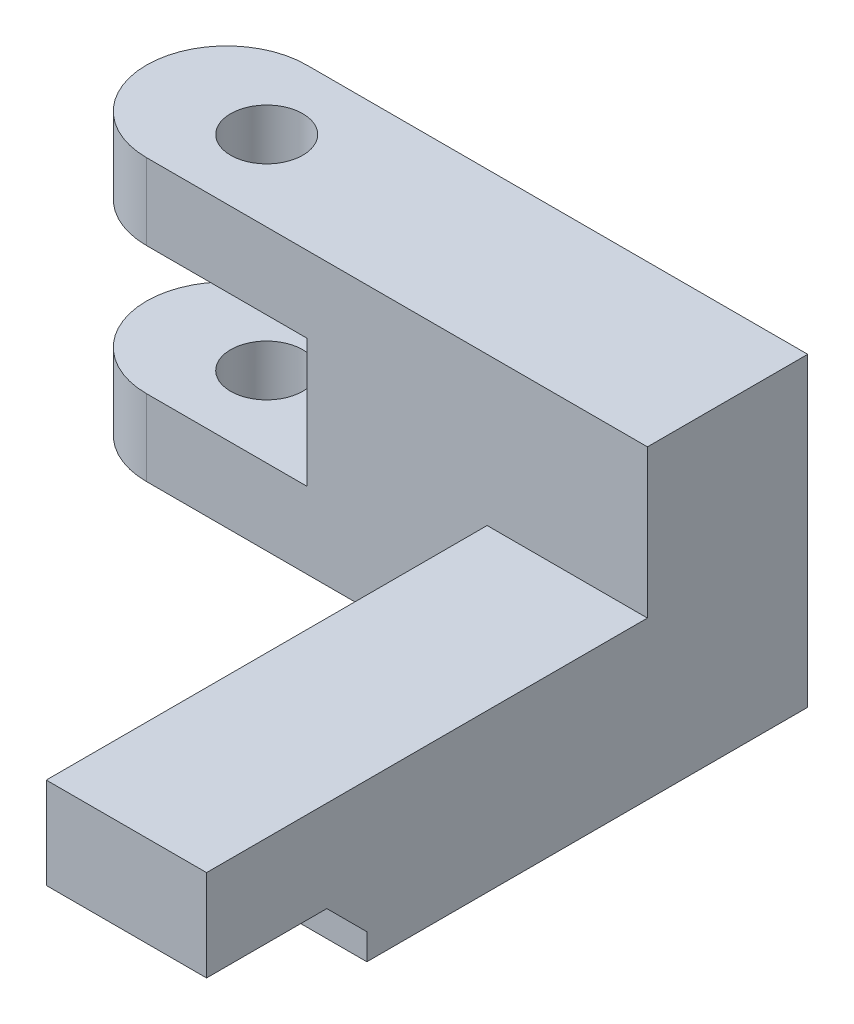
SolidWorks part; units mm, degrees
ref_plane "Front Plane" through (0, 0, 0) normal (0, 0, 1) x (1, 0, 0)
ref_plane "Top Plane" through (0, 0, 0) normal (0, 1, 0) x (1, 0, 0)
ref_plane "Right Plane" through (0, 0, 0) normal (1, 0, 0) x (0, 0, -1)
sketch "Sketch1" plane through (0, 0, 0) normal (0, 1, 0) x (1, 0, 0)
  line L1 (1.4969, 0) -> (13.9969, 0)
  line L3 (1.4969, -4) -> (9.9969, -4)
  line L5 (13.9969, 0) -> (13.9969, -15)
  line L10 (2.4969, -2) -> (13.9969, -2) construction
  line L11 (9.9969, -15) -> (13.9969, -15)
  line L16 (9.9969, -4) -> (9.9969, -15)
  circle A0 centre (2.4969, -2) radius 0.9
  arc A2 (1.4969, -4) -> (1.4969, 0) centre (1.4969, -2) cw
  dimension "D3" = 1.8
  dimension "D2" = 2
  dimension "D1" = 8.5
  dimension "D4" = 4
  dimension "D5" = 4
  dimension "D6" = 15
  dimension "D7" = 1
extrude "Boss-Extrude1" add sketch "Sketch1" along normal blind 7
sketch "Sketch2" plane through (0, 0, 4) normal (0, 0, 1) x (1, 0, 0)
  line L0 (1.4969, 7) -> (-0.5031, 7) construction
  line L1 (-0.5031, 1.9) -> (5.4969, 1.9)
  line L2 (-0.5031, 1.9) -> (-0.5031, 5.1)
  line L3 (-0.5031, 5.1) -> (5.4969, 5.1)
  line L4 (5.4969, 1.9) -> (5.4969, 5.1)
  line L5 (2.4969, 5.1) -> (2.4969, 1.9) construction
  line L6 (-0.5031, 3.5) -> (5.4969, 3.5) construction
  line L7 (-0.5031, 7) -> (-0.5031, 0) construction
  line L8 (-0.5031, 7) -> (-0.5031, 0) construction
  line L9 (-0.5031, 0) -> (1.4969, 0) construction
  point P6 (-0.5031, 3.5)
  point P228 (2.4969, 3.5)
  dimension "D1" = 3.2
  dimension "D2" = 6
extrude "Cut-Extrude1" cut sketch "Sketch2" against normal up to next
sketch "Sketch3" plane through (13.9969, 0, 0) normal (1, 0, 0) x (0, 0, -1)
  line L8 (-15, 3.5) -> (0, 3.5) construction
  line L9 (0, 7) -> (0, 0) construction
  line L14 (-15, 7) -> (-15, 0) construction
  line L16 (-15, 7) -> (-4, 7)
  line L17 (-15, 7) -> (-15, 3.3)
  line L18 (-15, 3.3) -> (-4, 3.3)
  line L19 (-4, 7) -> (-4, 3.3)
  line L20 (-9.5, 3.3) -> (-9.5, 7) construction
  line L21 (-15, 5.15) -> (-4, 5.15) construction
  point P230 (-9.5, 5.15)
  dimension "D1" = 4
  dimension "D2" = 0.2
extrude "Cut-Extrude2" cut sketch "Sketch3" against normal blind 4
sketch "Sketch6" plane through (0, 0, 0) normal (0, -1, 0) x (1, 0, 0)
  line L0 (9.9969, 4) -> (9.9969, 15) construction
  line L1 (13.9969, 0) -> (9.9969, 0)
  line L2 (13.9969, 0) -> (13.9969, 15)
  line L3 (13.9969, 15) -> (9.9969, 15)
  line L4 (9.9969, 0) -> (9.9969, 15)
  line L5 (11.9969, 15) -> (11.9969, 0) construction
  line L6 (13.9969, 7.5) -> (9.9969, 7.5) construction
  line L7 (9.9969, 15) -> (13.9969, 15) construction
  point P108 (11.9969, 7.5)
extrude "Boss-Extrude2" add sketch "Sketch6" along normal blind 0.6275
sketch "Sketch4" plane through (13.9969, 0, 0) normal (1, 0, 0) x (0, 0, -1)
  line L1 (-11, -0.6275) -> (-15, -0.6275)
  line L2 (-11, -0.6275) -> (-11, 0.0225)
  line L5 (-13, 1.0225) -> (-13, -0.6275) construction
  line L6 (-15, 1.0225) -> (-12, 1.0225)
  line L8 (-11, 0.0225) -> (-12, 1.0225)
  line L11 (0, -0.6275) -> (-15, -0.6275) construction
  line L13 (-15, 1.0225) -> (-15, -0.6275)
  line L14 (-15, 3.3) -> (-15, -0.6275) construction
  point P2 (-11.502, -0.3085)
  point P6 (-13, -0.5)
  dimension "D1" = 1.65
  dimension "D2" = 135
  dimension "D3" = 4
  dimension "D4" = 1
extrude "Cut-Extrude3" cut sketch "Sketch4" against normal up to next
equation "\"D1@Sketch1\"=7.5+\"D7@Sketch1\""
